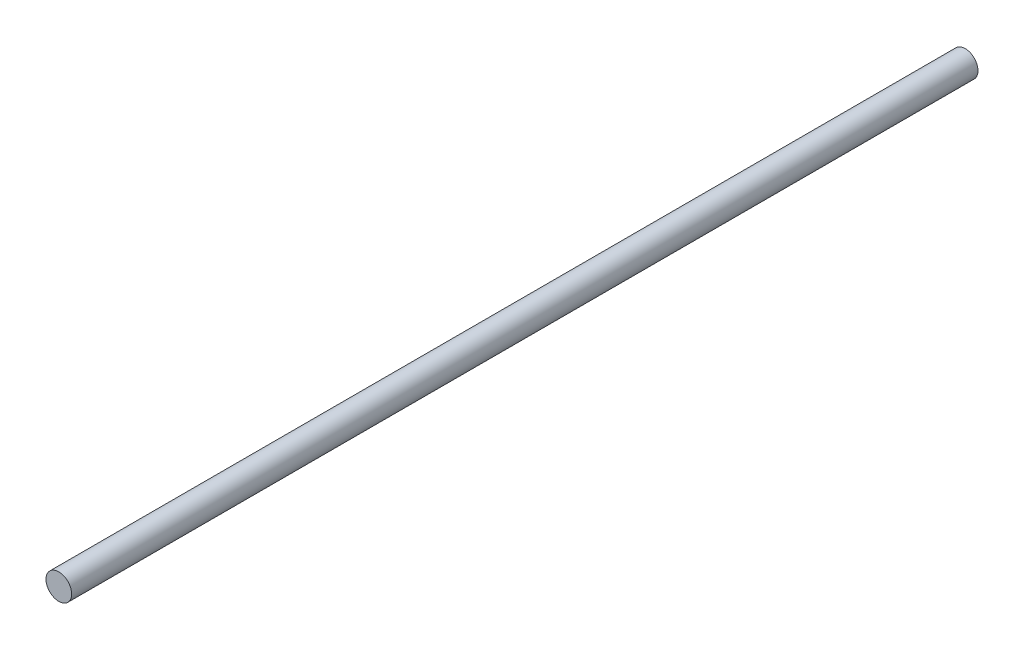
SolidWorks part; units mm, degrees
material "Aluminum"
ref_plane "Front Plane" through (0, 0, 0) normal (0, 0, 1) x (1, 0, 0)
ref_plane "Top Plane" through (0, 0, 0) normal (0, 1, 0) x (1, 0, 0)
ref_plane "Right Plane" through (0, 0, 0) normal (1, 0, 0) x (0, 0, -1)
sketch "Sketch1" plane through (0, 0, 0) normal (0, 0, 1) x (1, 0, 0)
  circle A0 centre (0, 0) radius 2.54
  dimension "D1" = 5.08
extrude "Boss-Extrude1" add sketch "Sketch1" along normal blind 179.5424 contours A0
equation "\"Diameter\"= .20in"
equation "\"Force\"= 400"
equation "\"Modulus\"= 10000000"
equation "\"Deflection\"= 0.009in"
equation "\"Area\"= PI * \"Diameter\" ^ 2 / 4"
equation "\"Length\"= \"Deflection\" * \"Area\" * \"Modulus\" / \"Force\""
